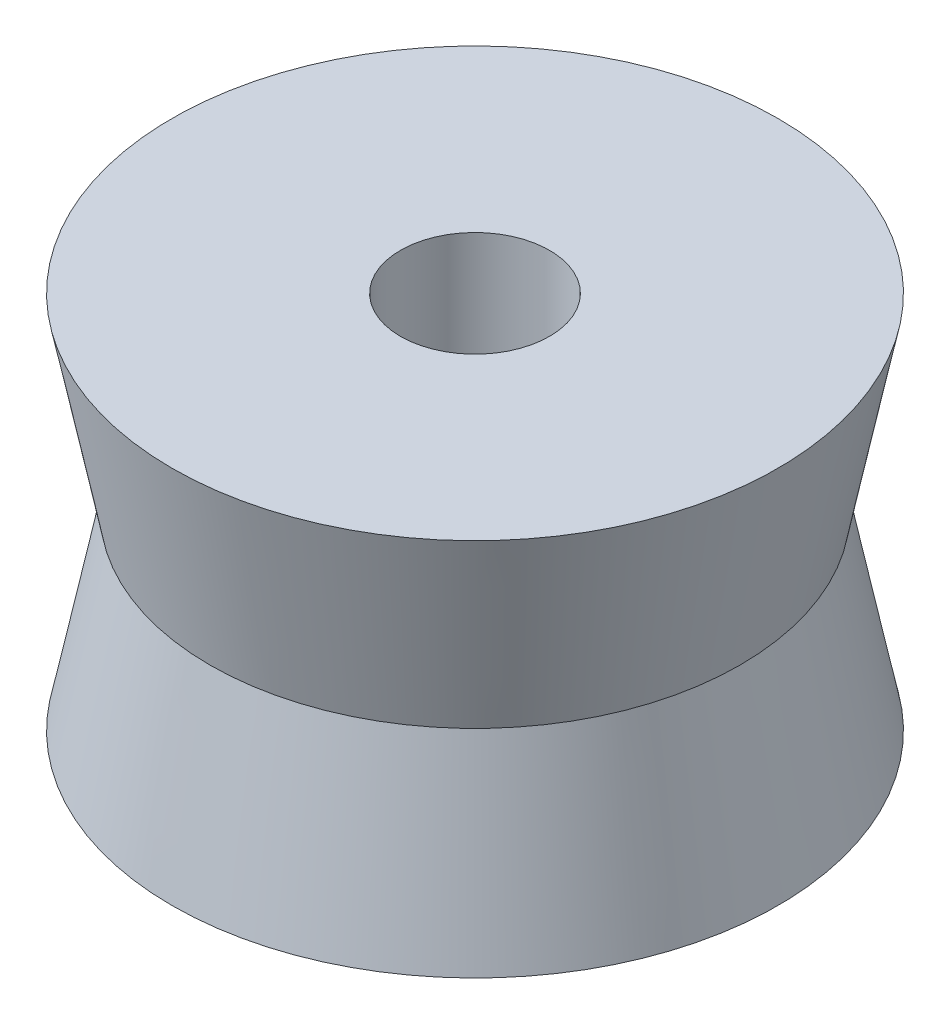
SolidWorks part; units mm, degrees
ref_plane "Front Plane" through (0, 0, 0) normal (0, 0, 1) x (1, 0, 0)
ref_plane "Top Plane" through (0, 0, 0) normal (0, 1, 0) x (1, 0, 0)
ref_plane "Right Plane" through (0, 0, 0) normal (1, 0, 0) x (0, 0, -1)
sketch "Sketch1" plane through (0, 0, 0) normal (1, 0, 0) x (0, 0, -1)
  line L0 (0, 0) -> (-3.81, 0)
  line L1 (-3.81, 0) -> (-3.81, 12.7)
  line L2 (-3.81, 12.7) -> (0, 12.7)
  line L3 (0, 12.7) -> (0, 0)
  line L5 (-3.81, 12.7) -> (-10.16, 12.7)
  line L6 (-3.81, 12.7) -> (-3.81, 0)
  line L7 (-3.81, 0) -> (-10.16, 0)
  line L8 (-10.16, 12.7) -> (-10.16, 0)
  line L10 (-8.89, 6.35) -> (-10.16, 12.7)
  line L11 (-10.16, 0) -> (-8.89, 6.35)
  line L12 (-2.5, 12.7) -> (-2.5, 0)
  dimension "D1" = 3.81
  dimension "D2" = 12.7
  dimension "D3" = 6.35
  dimension "D4" = 2.5
  dimension "D5" = 1.27
revolve "Revolve1" add sketch "Sketch1" angle 360 about L3
